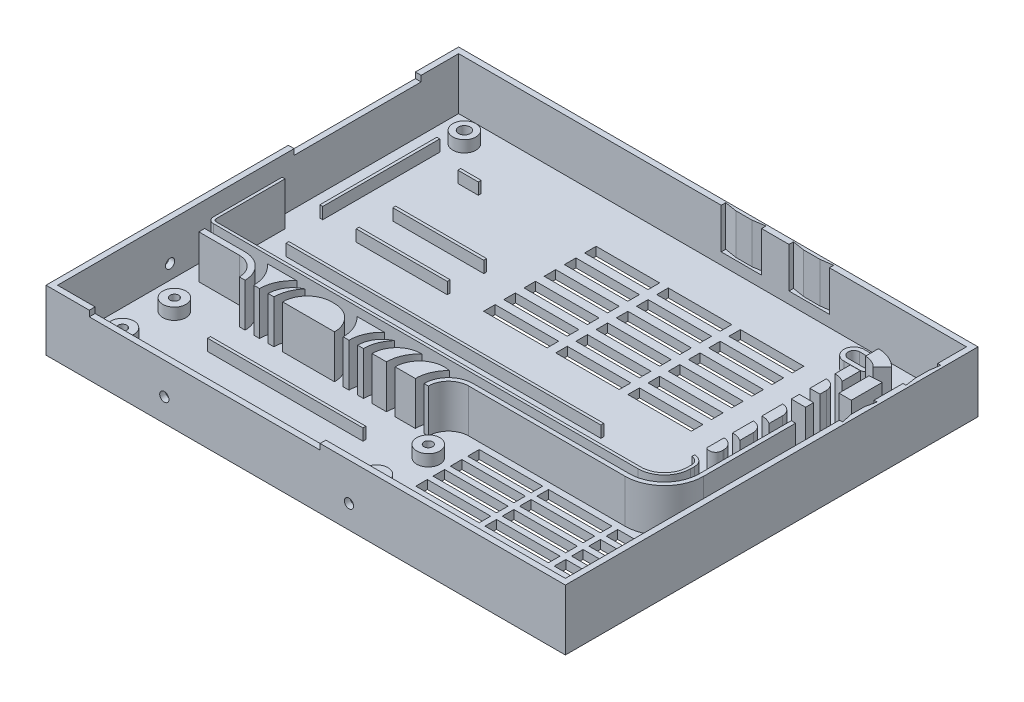
SolidWorks part; units mm, degrees
ref_plane "Front Plane" through (0, 0, 0) normal (0, 0, 1) x (1, 0, 0)
ref_plane "Top Plane" through (0, 0, 0) normal (0, 1, 0) x (1, 0, 0)
ref_plane "Right Plane" through (0, 0, 0) normal (1, 0, 0) x (0, 0, -1)
sketch "Sketch1" plane through (0, 0, 0) normal (0, 1, 0) x (1, 0, 0)
  line L0 (-67.5, 0) -> (67.5, 0) construction
  line L1 (0, 38) -> (0, -38) construction
  line L3 (-67.5, 38) -> (67.5, 38) construction
  line L4 (-67.5, 38) -> (-67.5, -38) construction
  line L5 (-67.5, -38) -> (67.5, -38) construction
  line L6 (67.5, 38) -> (67.5, -38) construction
  line L7 (-67.5, 38) -> (67.5, -38) construction
  line L8 (-67.5, -38) -> (67.5, 38) construction
  line L9 (-71, -71.5) -> (24, -71.5) construction
  line L10 (-23.5, -59) -> (-23.5, -84) construction
  line L11 (-38, -59) -> (-38, -71.5) construction
  line L12 (-17, -59) -> (-17, -71.5) construction
  line L13 (11, -59) -> (11, -71.5) construction
  line L14 (-79.5, 48) -> (-79.5, -95) construction
  line L16 (24, -59) -> (24, -84) construction
  line L17 (-79.5, -95) -> (100.5, -95) construction
  line L18 (100.5, -95) -> (100.5, 48) construction
  line L19 (-71, -59) -> (-71, -84) construction
  line L20 (-71, -84) -> (24, -84) construction
  line L21 (100.5, 48) -> (-79.5, 48) construction
  line L22 (-71, -59) -> (24, -59) construction
  line L23 (0, 38) -> (0, 42) construction
  line L24 (-71.5, 42) -> (71.5, 42) construction
  line L25 (-71.5, 42) -> (-71.5, -42) construction
  line L26 (-71.5, -42) -> (71.5, -42) construction
  line L27 (71.5, 42) -> (71.5, -42) construction
  line L28 (-67.5, 0) -> (-71.5, 0) construction
  line L29 (-43, -59) -> (-43, -71.5) construction
  line L30 (-48, -59) -> (-48, -71.5) construction
  line L31 (-12, -59) -> (-12, -71.5) construction
  line L32 (-7, -59) -> (-7, -71.5) construction
  line L33 (1, -59) -> (1, -71.5) construction
  line L34 (67.5, 38) -> (72.7, 38) construction
  line L35 (67.5, 40) -> (72.7, 40)
  line L36 (67.5, 36) -> (72.7, 36)
  line L37 (67.5, -38) -> (72.6846, -38.4) construction
  line L40 (67.6538, -36.0059) -> (72.8384, -36.4059)
  line L41 (67.3462, -39.9941) -> (72.5307, -40.3941)
  line L42 (-67.5, -38) -> (-67.5, -38.4) construction
  line L43 (-65.5, -38) -> (-65.5, -38.4)
  line L44 (-69.5, -38) -> (-69.5, -38.4)
  circle A0 centre (-67.5, 38) radius 2
  circle A4 centre (-67.5, -62.5) radius 1.5
  circle A8 centre (20.5, -62.5) radius 1.5
  circle A9 centre (20.5, -80.5) radius 1.5
  circle A10 centre (-67.5, -80.5) radius 1.5
  arc A11 (67.5, 40) -> (67.5, 36) centre (67.5, 38) ccw
  arc A12 (72.7, 36) -> (72.7, 40) centre (72.7, 38) ccw
  arc A15 (67.6538, -36.0059) -> (67.3462, -39.9941) centre (67.5, -38) ccw
  arc A16 (72.5307, -40.3941) -> (72.8384, -36.4059) centre (72.6846, -38.4) ccw
  arc A17 (-65.5, -38) -> (-69.5, -38) centre (-67.5, -38) ccw
  arc A18 (-69.5, -38.4) -> (-65.5, -38.4) centre (-67.5, -38.4) ccw
  point P5 (0, 0)
  point P11 (70.1, 38)
  point P13 (-67.5, -38.2)
  point P14 (-23.5, -70)
  point P27 (0, 0)
  point P62 (70.0923, -38.2)
  dimension "D3" = 4
  dimension "D6" = 84
  dimension "D1" = 76
  dimension "D2" = 135
  dimension "D4" = 18
  dimension "D5" = 88
  dimension "D7" = 143
  dimension "D8" = 25
  dimension "D9" = 95
  dimension "D10" = 17
  dimension "D11" = 28
  dimension "D12" = 33
  dimension "D13" = 54
  dimension "D14" = 82
  dimension "D15" = 14.5
  dimension "D16" = 10
  dimension "D17" = 12
  dimension "D18" = 33
  dimension "D19" = 23
  dimension "D20" = 59
  dimension "D21" = 64
  dimension "D22" = 72
  dimension "D23" = 5.2
  dimension "D24" = 4
  dimension "D25" = 4
  dimension "D26" = 5.2
  dimension "D27" = 4
  dimension "D28" = 0.4
  dimension "D29" = 0.4
sketch "CablePath" plane through (0, 0, 0) normal (0, 1, 0) x (1, 0, 0)
  line L0 (-12, -59) -> (-12, -56) construction
  line L5 (101, -94.5) -> (101, 47)
  line L6 (101, 47) -> (-79, 47)
  line L8 (-43, -56) -> (-43, -70.139) construction
  line L9 (-75.5, -42.5222) -> (-75.5, -18.6789) construction
  line L12 (71.5, -29) -> (80.8048, -29) construction
  line L16 (-71.5, -42) -> (71.5, -42) construction
  line L18 (71.5, -18.84) -> (80.8048, -18.84) construction
  line L21 (80.8048, -51.7714) -> (80.8048, 34.0145) construction
  line L22 (30.5, -56) -> (-60.9203, -56) construction
  line L23 (-10.5, -56) -> (-8.5, -56)
  line L24 (71.5, 40.5) -> (71.5, -42) construction
  line L25 (1, -59) -> (1, -56) construction
  line L26 (85.8048, -3.52) -> (85.8048, -35.359) construction
  line L27 (-79, 47) -> (-79, -94.5)
  line L28 (11, -59) -> (11, -56) construction
  line L29 (-79, -94.5) -> (101, -94.5)
  line L30 (-38, -70.139) -> (-38, -56) construction
  line L31 (-43, -59) -> (-43, -71.5) construction
  line L32 (-38, -59) -> (-38, -71.5) construction
  line L33 (71.5, 1.48) -> (80.8048, 1.48) construction
  line L34 (-58, -44.5) -> (-72.0222, -44.5)
  line L35 (75.1637, -46) -> (-33, -46) construction
  line L36 (84.3048, -3.52) -> (84.3048, -8.2028)
  line L37 (-71, -59) -> (24, -59) construction
  line L38 (75.1637, -44.5) -> (-33, -44.5)
  line L39 (71.5, -8.68) -> (80.8048, -8.68) construction
  line L40 (87.3048, -3.52) -> (87.3048, -35.359)
  line L41 (21, -47.5) -> (75.1637, -47.5)
  line L42 (84.3048, -13.68) -> (84.3048, -18.3628)
  line L43 (84.3048, -23.84) -> (84.3048, -24.2165)
  line L44 (84.3048, -3.52) -> (84.3048, -35.359) construction
  line L45 (84.3048, -34) -> (84.3048, -35.359)
  line L46 (-27.8976, -47.4999) -> (-26.899, -47.4999)
  line L47 (75.1637, -47.5) -> (-33, -47.5) construction
  line L48 (2.5, -56) -> (9.5, -56)
  line L49 (-41.5, -56) -> (-39.5, -56)
  line L50 (-36.5, -56) -> (-18.5, -56)
  line L51 (-17, -59) -> (-17, -71.5) construction
  line L52 (21, -49) -> (75.1637, -49)
  line L53 (88.8048, -3.52) -> (88.8048, -35.359)
  line L54 (83.3048, -34) -> (83.3048, -35.359)
  line L55 (75.1637, -43.5) -> (-33, -43.5)
  line L56 (12.5, -56) -> (14, -56)
  line L57 (-58, -46) -> (-72.0222, -46) construction
  line L58 (80.8048, 2.98) -> (80.8048, 5.7849)
  line L59 (80.8048, -0.02) -> (80.8048, -7.18)
  line L60 (80.8048, -10.18) -> (80.8048, -17.34)
  line L61 (80.8048, -20.34) -> (80.8048, -26.2952)
  line L62 (80.8048, -30.5) -> (80.8048, -31.5)
  line L63 (-74, -42.5222) -> (-74, -18.6789)
  line L64 (80.8048, 5.7849) -> (85.7673, 5.7849)
  line L65 (85.7673, 5.7849) -> (85.7673, 2.98)
  line L66 (85.7673, 2.98) -> (80.8048, 2.98)
  line L67 (87.3048, -3.52) -> (88.8048, -3.52)
  line L68 (-7, -59) -> (-7, -56) construction
  line L69 (-17, -59) -> (-17, -56) construction
  line L70 (-48, -59) -> (-48, -56) construction
  line L71 (-58, -43.5) -> (-72.0222, -43.5)
  line L72 (-73, -42.5222) -> (-73, -18.6789)
  line L73 (11, -59) -> (11, -71.5) construction
  line L74 (-58, -47.5) -> (-72.0222, -47.5)
  line L75 (-58, -49.5) -> (-72.0222, -49.5)
  line L76 (-51.5, -56) -> (-49.5, -56)
  line L77 (-72.0222, -47.5) -> (-72.0222, -49.5)
  line L78 (-58, -43.5) -> (-33, -43.5)
  line L79 (-74, -18.6789) -> (-73, -18.6789)
  line L80 (-46.5, -56) -> (-44.5, -56)
  line L81 (-19.2537, -47.5) -> (-9.746, -47.5)
  line L82 (-40.38, -47.1804) -> (-50.62, -47.1804)
  line L83 (-58, -44.5) -> (-33, -44.5)
  line L84 (-15.5, -56) -> (-13.5, -56)
  line L85 (3, -47.5) -> (3.254, -47.5)
  line L86 (-5.5, -56) -> (-0.5, -56)
  line L87 (-71.5, 42) -> (-71.5, -42) construction
  line L88 (67.5, 16.6233) -> (80.8048, 16.6233) construction
  line L89 (67.5, 27.1917) -> (80.8048, 27.1917) construction
  line L90 (67.5, 6.7426) -> (83.9849, 6.7426) construction
  line L91 (85.8048, -3.52) -> (85.8048, 11.6233) construction
  line L92 (85.8048, 11.6233) -> (85.8048, 22.1917) construction
  line L93 (80.8048, 33.1917) -> (80.8048, 28.6917)
  line L94 (85.4191, 26.7697) -> (88.5829, 29.9699)
  line L95 (87.3048, 13.0166) -> (87.3048, 23.4421)
  line L96 (87.3048, 23.4421) -> (91.5804, 23.7236)
  line L97 (84.3065, 23.4421) -> (84.3055, 17.1)
  line L98 (84.3044, 9.4184) -> (80.8048, 9.4184)
  line L99 (80.8048, 9.4184) -> (80.8048, 15.1233)
  line L100 (84.3048, 11.6233) -> (84.3044, 9.4184)
  line L101 (80.8048, 18.1233) -> (80.8048, 23.4421)
  line L102 (91.5804, 23.7236) -> (91.5804, 13.0166)
  line L103 (91.5804, 13.0166) -> (87.3048, 13.0166)
  line L104 (84.3065, 23.4421) -> (80.8048, 23.4421)
  arc A0 (14, -56) -> (21, -49) centre (21, -56) cw
  circle A1 centre (-67.5, -62.5) radius 1.5 construction
  arc A2 (9.5, -56) -> (21, -44.5) centre (21, -56) cw construction
  arc A3 (75.1637, -49) -> (88.8048, -35.359) centre (75.1637, -35.359) ccw
  arc A4 (85.4191, 26.7697) -> (80.8048, 28.6917) centre (80.8048, 22.1917) ccw
  arc A5 (88.5829, 29.9699) -> (80.8048, 33.1917) centre (80.8048, 22.1917) ccw
  arc A7 (84.3055, 17.1) -> (80.8048, 18.1233) centre (80.8048, 11.6233) ccw
  circle A8 centre (-67.5, -80.5) radius 1.5 construction
  circle A9 centre (-67.5, -62.5) radius 1.5
  circle A10 centre (20.5, -62.5) radius 1.5 construction
  circle A11 centre (-67.5, -80.5) radius 1.5
  arc A12 (80.8048, -26.2952) -> (84.3048, -24.2165) centre (82.1448, -24.5655) ccw
  arc A13 (85.8048, 22.1917) -> (80.8048, 27.1917) centre (80.8048, 22.1917) ccw construction
  arc A14 (85.8048, 11.6233) -> (80.8048, 16.6233) centre (80.8048, 11.6233) ccw construction
  arc A15 (84.3048, 11.6233) -> (80.8048, 15.1233) centre (80.8048, 11.6233) ccw
  arc A16 (80.8048, 1.48) -> (85.8048, -3.52) centre (80.8048, -3.52) cw construction
  arc A17 (80.8048, -8.68) -> (85.8048, -13.68) centre (80.8048, -13.68) cw construction
  arc A18 (80.8048, -18.84) -> (85.8048, -23.84) centre (80.8048, -23.84) cw construction
  arc A19 (80.8048, -29) -> (85.8048, -34) centre (80.8048, -34) cw construction
  arc A20 (75.1637, -46) -> (85.8048, -35.359) centre (75.1637, -35.359) ccw construction
  arc A21 (-43, -56) -> (-33, -46) centre (-33, -56) cw construction
  arc A22 (-38, -56) -> (-27.8796, -46) centre (-27.9993, -56) cw construction
  arc A23 (1, -56) -> (11, -46) centre (11, -56) cw construction
  arc A24 (11, -56) -> (21, -46) centre (21, -56) cw construction
  circle A25 centre (20.5, -62.5) radius 1.5
  circle A26 centre (20.5, -80.5) radius 1.5 construction
  circle A27 centre (20.5, -80.5) radius 1.5
  arc A28 (80.8048, -0.02) -> (84.3048, -3.52) centre (80.8048, -3.52) cw
  arc A29 (75.1637, -44.5) -> (84.3048, -35.359) centre (75.1637, -35.359) ccw
  arc A30 (-44.5, -56) -> (-40.38, -47.1804) centre (-33, -56) cw
  arc A31 (80.8048, -10.18) -> (84.3048, -13.68) centre (80.8048, -13.68) cw
  arc A32 (80.8048, -20.34) -> (84.3048, -23.84) centre (80.8048, -23.84) cw
  arc A33 (80.8048, -30.5) -> (84.3048, -34) centre (80.8048, -34) cw
  arc A34 (12.5, -56) -> (21, -47.5) centre (21, -56) cw
  arc A35 (2.5, -56) -> (13, -47.7386) centre (11, -56) cw
  arc A36 (-36.5, -56) -> (-27.8976, -47.4999) centre (-27.9993, -56) cw
  arc A37 (80.8048, 2.98) -> (87.3048, -3.52) centre (80.8048, -3.52) cw construction
  arc A38 (75.1637, -47.5) -> (87.3048, -35.359) centre (75.1637, -35.359) ccw
  arc A39 (-41.5, -56) -> (-36.5004, -48.2542) centre (-33, -56) cw
  arc A40 (80.8048, -7.18) -> (84.3048, -8.2028) centre (80.8048, -13.68) cw
  arc A41 (80.8048, -17.34) -> (84.3048, -18.3628) centre (80.8048, -23.84) cw
  arc A43 (9.5, -56) -> (13, -47.7386) centre (21, -56) cw
  arc A44 (-0.5, -56) -> (3.254, -47.5) centre (11, -56) cw
  arc A45 (-39.5, -56) -> (-36.5004, -48.2542) centre (-27.9993, -56) cw
  arc A46 (-39.5, -56) -> (-27.8617, -44.5001) centre (-27.9993, -56) cw construction
  arc A47 (87.3048, 11.6233) -> (80.8048, 18.1233) centre (80.8048, 11.6233) ccw construction
  arc A48 (80.8048, -7.18) -> (87.3048, -13.68) centre (80.8048, -13.68) cw construction
  arc A49 (80.8048, -17.34) -> (87.3048, -23.84) centre (80.8048, -23.84) cw construction
  arc A50 (80.8048, 4.48) -> (88.8048, -3.52) centre (80.8048, -3.52) cw construction
  arc A51 (-0.5, -56) -> (11, -44.5) centre (11, -56) cw construction
  arc A52 (80.8048, -31.5) -> (83.3048, -34) centre (80.8048, -34) cw
  arc A53 (75.1637, -43.5) -> (83.3048, -35.359) centre (75.1637, -35.359) ccw
  arc A54 (-48, -56) -> (-58, -46) centre (-58, -56) ccw construction
  arc A55 (-17, -56) -> (-26.881, -46) centre (-27.0007, -56) ccw construction
  arc A56 (-41.5, -56) -> (-33, -47.5) centre (-33, -56) cw construction
  arc A57 (-45.5, -56) -> (-33, -43.5) centre (-33, -56) cw construction
  arc A58 (-72.0222, -46) -> (-75.5, -42.5222) centre (-72.0222, -42.5222) cw construction
  arc A59 (-46.5, -56) -> (-50.62, -47.1804) centre (-58, -56) ccw
  arc A60 (-72.0222, -44.5) -> (-74, -42.5222) centre (-72.0222, -42.5222) cw
  arc A61 (-15.5, -56) -> (-19.2537, -47.5) centre (-27.0007, -56) ccw
  arc A62 (-72.0222, -43.5) -> (-73, -42.5222) centre (-72.0222, -42.5222) cw
  arc A63 (-49.5, -56) -> (-58, -47.5) centre (-58, -56) ccw
  arc A64 (-51.5, -56) -> (-58, -49.5) centre (-58, -56) ccw
  arc A65 (-45.5, -56) -> (-58, -43.5) centre (-58, -56) ccw construction
  arc A66 (-18.5, -56) -> (-26.899, -47.4999) centre (-27.0007, -56) ccw
  arc A67 (-12, -56) -> (-2, -46) centre (-2, -56) cw construction
  arc A68 (-15.5, -56) -> (-26.8631, -44.5001) centre (-27.0007, -56) ccw construction
  arc A69 (-46.5, -56) -> (-58, -44.5) centre (-58, -56) ccw construction
  arc A70 (-44.5, -56) -> (-33, -44.5) centre (-33, -56) cw construction
  arc A71 (2.5, -56) -> (11, -47.5) centre (11, -56) cw construction
  arc A72 (-7, -56) -> (3, -46) centre (3, -56) cw construction
  arc A73 (-10.5, -56) -> (-5.5, -48.254) centre (-2, -56) cw
  arc A74 (-5.5, -56) -> (3, -47.5) centre (3, -56) cw
  arc A75 (-13.5, -56) -> (-9.746, -47.5) centre (-2, -56) cw
  arc A76 (-8.5, -56) -> (-5.5, -48.254) centre (3, -56) cw
  arc A77 (87.3048, 22.1917) -> (80.8048, 28.6917) centre (80.8048, 22.1917) ccw construction
  arc A78 (-13.5, -56) -> (-2, -44.5) centre (-2, -56) cw construction
  arc A79 (-10.5, -56) -> (-2, -47.5) centre (-2, -56) cw construction
  arc A80 (91.8048, 22.1917) -> (80.8048, 33.1917) centre (80.8048, 22.1917) ccw construction
  arc A81 (-8.5, -56) -> (3, -44.5) centre (3, -56) cw construction
  point P0 (67.5, -38)
  point P7 (67.5, 38)
  point P10 (-67.5, -80.5)
  point P117 (77.6351, -51.5)
  point P118 (-14.035, -51.5)
  point P127 (77.6351, -54.5)
  point P128 (-14.035, -54.5)
  point P132 (79.6209, -33.364)
  point P134 (85.4849, -33.364)
  point P137 (3.3488, -47.5)
  point P138 (3.3488, -61)
  point P139 (-10.1512, -61)
  point P146 (3.3488, -50.5)
  point P147 (3.3488, -61)
  point P148 (-7.1512, -61)
  point P154 (80.8048, 22.2244)
  point P242 (3.4721, -55.4721)
  point P243 (-8, -55.4721)
  point P244 (3.4721, -44)
  point P253 (87.3048, 22.2244)
  point P256 (80.8048, 22.2244)
  point P257 (91.8048, 22.2244)
  dimension "D5" = 10.16
  dimension "D8" = 3
  dimension "D23" = 1.5
  dimension "D24" = 5
  dimension "D25" = 5
  dimension "D1" = 1.5
  dimension "D3" = 4
  dimension "D4" = 13
  dimension "D6" = 10.16
  dimension "D7" = 10.16
  dimension "D9" = 3.5
  dimension "D10" = 1.5
  dimension "D11" = 1.5
  dimension "D12" = 1
  dimension "D13" = 1.5
  dimension "D14" = 1
  dimension "D15" = 1.5
  dimension "D16" = 2
  dimension "D17" = 1.5
  dimension "D18" = 1.5
  dimension "D28" = 180
  dimension "D19" = 1.5
  dimension "D20" = 1.5
  dimension "D21" = 1.5
  dimension "D22" = 1.5
  dimension "D26" = 1.5
  dimension "D27" = 6
  dimension "D30" = 1.5
  dimension "D31" = 1.5
sketch "Bottom" plane through (0, 0, 0) normal (0, 1, 0) x (1, 0, 0)
  line L0 (-79.5, 48) -> (-79.5, -95) construction
  line L1 (-79.5, 48) -> (-79.5, -95)
  line L2 (-79.5, -95) -> (100.5, -95) construction
  line L3 (-79.5, -95) -> (100.5, -95)
  line L4 (67.6538, -36.0059) -> (72.8384, -36.4059) construction
  line L5 (67.3462, -39.9941) -> (72.5307, -40.3941) construction
  line L6 (100.5, -95) -> (100.5, 48) construction
  line L7 (100.5, -95) -> (100.5, 48)
  line L8 (100.5, 48) -> (-79.5, 48) construction
  line L9 (100.5, 48) -> (-79.5, 48)
  line L10 (67.6538, -36.0059) -> (72.8384, -36.4059)
  line L11 (67.3462, -39.9941) -> (72.5307, -40.3941)
  line L12 (67.5, 36) -> (72.7, 36) construction
  line L13 (67.5, 40) -> (72.7, 40) construction
  line L14 (67.5, 36) -> (72.7, 36)
  line L15 (67.5, 40) -> (72.7, 40)
  line L16 (-65.5, -38) -> (-65.5, -38.4) construction
  line L17 (-69.5, -38) -> (-69.5, -38.4) construction
  line L18 (-65.5, -38) -> (-65.5, -38.4)
  line L19 (-69.5, -38) -> (-69.5, -38.4)
  arc A0 (72.5307, -40.3941) -> (72.8384, -36.4059) centre (72.6846, -38.4) ccw construction
  arc A1 (67.6538, -36.0059) -> (67.3462, -39.9941) centre (67.5, -38) ccw construction
  arc A2 (72.5307, -40.3941) -> (72.8384, -36.4059) centre (72.6846, -38.4) ccw
  arc A3 (67.6538, -36.0059) -> (67.3462, -39.9941) centre (67.5, -38) ccw
  arc A4 (72.7, 36) -> (72.7, 40) centre (72.7, 38) ccw construction
  arc A5 (67.5, 40) -> (67.5, 36) centre (67.5, 38) ccw construction
  arc A6 (72.7, 36) -> (72.7, 40) centre (72.7, 38) ccw
  arc A7 (67.5, 40) -> (67.5, 36) centre (67.5, 38) ccw
  circle A8 centre (-67.5, 38) radius 2 construction
  circle A9 centre (-67.5, 38) radius 2
  arc A10 (-69.5, -38.4) -> (-65.5, -38.4) centre (-67.5, -38.4) ccw construction
  arc A11 (-65.5, -38) -> (-69.5, -38) centre (-67.5, -38) ccw construction
  arc A12 (-69.5, -38.4) -> (-65.5, -38.4) centre (-67.5, -38.4) ccw
  arc A13 (-65.5, -38) -> (-69.5, -38) centre (-67.5, -38) ccw
  dimension "D1" = 143
  dimension "D2" = 180
extrude "Boss-Bottom" add sketch "Bottom" along normal blind 3
sketch "PCBmount" plane through (0, 3, 0) normal (0, 1, 0) x (1, 0, 0)
  line L0 (-49.5761, -67.9069) -> (-49.5761, -68.9069)
  line L1 (-49.5761, -67.9069) -> (4.2504, -67.9069)
  line L2 (-49.5761, -68.9069) -> (4.2504, -68.9069)
  line L3 (4.2504, -67.9069) -> (4.2504, -68.9069)
  line L5 (-64.5007, -25.8146) -> (44.6202, -25.8146)
  line L6 (-64.5007, -25.8146) -> (-64.5007, -26.8146)
  line L7 (44.6202, -25.8146) -> (44.6202, -26.8146)
  line L8 (-64.5007, -26.8146) -> (44.6202, -26.8146)
  line L9 (-56.6714, -10.3272) -> (-25.1095, -10.3272)
  line L10 (-56.6714, -10.3272) -> (-56.6714, -9.3272)
  line L11 (-25.1095, -10.3272) -> (-25.1095, -9.3272)
  line L12 (-56.6714, -9.3272) -> (-25.1095, -9.3272)
  line L13 (-56.6714, 2.3448) -> (-25.1095, 2.3448)
  line L14 (-56.6714, 2.3448) -> (-56.6714, 3.3448)
  line L15 (-25.1095, 2.3448) -> (-25.1095, 3.3448)
  line L16 (-56.6714, 3.3448) -> (-25.1095, 3.3448)
  line L17 (-70.1846, -9.4098) -> (-69.1846, -9.4098)
  line L18 (-70.1846, -9.4098) -> (-70.1846, 31.1536)
  line L19 (-69.1846, -9.4098) -> (-69.1846, 31.1536)
  line L20 (-70.1846, 31.1536) -> (-69.1846, 31.1536)
  line L21 (-56.6714, 24.8918) -> (-49.5761, 24.8918)
  line L22 (-56.6714, 24.8918) -> (-56.6714, 25.8918)
  line L23 (-49.5761, 24.8918) -> (-49.5761, 25.8918)
  line L24 (-56.6714, 25.8918) -> (-49.5761, 25.8918)
  line L30 (67.5, 36) -> (72.7, 36) construction
  line L31 (67.5, 40) -> (72.7, 40) construction
  line L32 (-67.5, 0) -> (67.5, 0) construction
  line L33 (-67.5, 0) -> (67.5, 0) construction
  line L34 (67.5, 36) -> (72.7, 36)
  line L35 (67.5, 40) -> (72.7, 40)
  line L38 (-65.5, -38) -> (-65.5, -38.4) construction
  line L39 (-69.5, -38) -> (-69.5, -38.4) construction
  line L40 (-65.5, -38) -> (-65.5, -38.4)
  line L41 (-69.5, -38) -> (-69.5, -38.4)
  line L42 (-64, -38) -> (-64, -38.4)
  line L43 (-71, -38) -> (-71, -38.4)
  line L44 (67.5, 34.5) -> (72.7, 34.5)
  line L45 (67.5, 41.5) -> (72.7, 41.5)
  line L46 (67.6538, -36.0059) -> (72.8384, -36.4059) construction
  line L47 (67.3462, -39.9941) -> (72.5307, -40.3941) construction
  line L48 (67.6538, -36.0059) -> (72.8384, -36.4059)
  line L49 (67.3462, -39.9941) -> (72.5307, -40.3941)
  line L50 (67.7692, -34.5104) -> (72.9538, -34.9104)
  line L51 (67.2308, -41.4896) -> (72.4154, -41.8896)
  circle A4 centre (-67.5, -62.5) radius 1.5 construction
  circle A6 centre (-67.5, 38) radius 2 construction
  circle A8 centre (20.5, -80.5) radius 1.5 construction
  circle A9 centre (20.5, -62.5) radius 1.5 construction
  arc A10 (72.7, 36) -> (72.7, 40) centre (72.7, 38) ccw construction
  circle A11 centre (-67.5, -80.5) radius 1.5 construction
  circle A12 centre (-67.5, -62.5) radius 1.5
  arc A13 (-65.5, -38) -> (-69.5, -38) centre (-67.5, -38) ccw construction
  circle A14 centre (-67.5, 38) radius 2
  circle A16 centre (-67.5, 38) radius 4
  arc A17 (67.5, 40) -> (67.5, 36) centre (67.5, 38) ccw construction
  arc A18 (72.7, 36) -> (72.7, 40) centre (72.7, 38) ccw
  arc A19 (-69.5, -38.4) -> (-65.5, -38.4) centre (-67.5, -38.4) ccw construction
  circle A20 centre (-67.5, -62.5) radius 4
  circle A21 centre (-67.5, -80.5) radius 4
  circle A22 centre (20.5, -80.5) radius 4
  circle A23 centre (20.5, -62.5) radius 4
  circle A24 centre (-67.5, -80.5) radius 1.5
  circle A25 centre (20.5, -80.5) radius 1.5
  circle A26 centre (20.5, -62.5) radius 1.5
  arc A27 (67.5, 40) -> (67.5, 36) centre (67.5, 38) ccw
  arc A30 (-65.5, -38) -> (-69.5, -38) centre (-67.5, -38) ccw
  arc A31 (-69.5, -38.4) -> (-65.5, -38.4) centre (-67.5, -38.4) ccw
  arc A32 (-71, -38.4) -> (-64, -38.4) centre (-67.5, -38.4) ccw
  arc A33 (-64, -38) -> (-71, -38) centre (-67.5, -38) ccw
  arc A34 (72.7, 34.5) -> (72.7, 41.5) centre (72.7, 38) ccw
  arc A35 (67.5, 41.5) -> (67.5, 34.5) centre (67.5, 38) ccw
  arc A36 (72.5307, -40.3941) -> (72.8384, -36.4059) centre (72.6846, -38.4) ccw construction
  arc A37 (67.6538, -36.0059) -> (67.3462, -39.9941) centre (67.5, -38) ccw construction
  arc A38 (72.5307, -40.3941) -> (72.8384, -36.4059) centre (72.6846, -38.4) ccw
  arc A39 (67.6538, -36.0059) -> (67.3462, -39.9941) centre (67.5, -38) ccw
  arc A40 (72.4154, -41.8896) -> (72.9538, -34.9104) centre (72.6846, -38.4) ccw
  arc A41 (67.7692, -34.5104) -> (67.2308, -41.4896) centre (67.5, -38) ccw
  dimension "D1" = 8
  dimension "D2" = 8
  dimension "D3" = 1
  dimension "D5" = 1.5
  dimension "D6" = 1.5
  dimension "D4" = 1.5
extrude "Boss-PCBmount" add sketch "PCBmount" along normal blind 4
sketch "Sides" plane through (0, 3, 0) normal (0, 1, 0) x (1, 0, 0)
  line L0 (-79.5, -95) -> (100.5, -95) construction
  line L1 (100.5, -95) -> (100.5, 48) construction
  line L2 (-79.5, 48) -> (-79.5, -95) construction
  line L3 (100.5, 48) -> (-79.5, 48) construction
  line L4 (-79.5, -95) -> (100.5, -95)
  line L5 (100.5, -95) -> (100.5, 48)
  line L6 (-79.5, 48) -> (-79.5, -95)
  line L7 (100.5, 48) -> (-79.5, 48)
  line L8 (-77.5, -93) -> (98.5, -93)
  line L9 (98.5, -93) -> (98.5, 46)
  line L10 (98.5, 46) -> (-77.5, 46)
  line L11 (-77.5, 46) -> (-77.5, -93)
  dimension "D1" = 2
extrude "Boss-Sides" add sketch "Sides" along normal blind 18
sketch "24VHeatBedTabort" plane through (100.5, 0, 0) normal (1, 0, 0) x (0, 0, -1)
  line L0 (36, 21) -> (36, 9)
  line L1 (48, 21) -> (48, 0) construction
  line L2 (36, 9) -> (24, 9)
  line L3 (24, 9) -> (24, 21)
  line L4 (24, 21) -> (36, 21)
  line L5 (14, 21) -> (14, 9)
  line L6 (14, 9) -> (2, 9)
  line L7 (2, 9) -> (2, 21)
  line L8 (2, 21) -> (14, 21)
  line L10 (-95, 21) -> (48, 21) construction
  dimension "D3" = 12
  dimension "D5" = 12
  dimension "D6" = 10
extrude "Boss-CablePath" add sketch "CablePath" along normal blind 18 contours A74 L85 A44 L86 | A76 A73 L23 | A75 L81 A61 L84 | L38 L83 L34 A60 L63 L79 L72 A62 L71 L78 L55 A53 L54 A52 L62 A33 L45 A29 | A66 L46 A36 L50 | A35 A43 L48 | A34 L41 A38 L40 L67 L53 A3 L52 A0 L56 | L75 L77 L74 A63 L76 A64 | A59 L82 A30 L80 | A39 A45 L49 | L43 A12 L61 A32 | L42 A41 L60 A31 | L36 A40 L59 A28 | L65 L66 L58 L64 | L100 L98 L99 A15 | L97 A7 L101 L104 | L93 A4 L94 A5 | L102 L103 L95 L96
sketch "Fan" plane through (0, 3, 0) normal (0, 1, 0) x (1, 0, 0)
  line L1 (55.5, -50) -> (95.5, -50) construction
  line L2 (55.5, -50) -> (55.5, -90) construction
  line L3 (55.5, -90) -> (95.5, -90) construction
  line L4 (95.5, -50) -> (95.5, -90) construction
  line L5 (55.5, -50) -> (95.5, -90) construction
  line L6 (55.5, -90) -> (95.5, -50) construction
  line L8 (98.5, -93) -> (98.5, 46) construction
  line L9 (-77.5, -93) -> (98.5, -93) construction
  circle A0 centre (75.5, -70) radius 19
  circle A1 centre (75.5, -70) radius 10
  arc A2 (75.5, -70) -> (75.5, -51) centre (80.3261, -60.5) cw
  arc A3 (75.5, -70) -> (91.9545, -60.5) centre (86.1403, -69.4295) cw
  arc A4 (75.5, -70) -> (91.9545, -79.5) centre (81.3142, -78.9295) cw
  arc A5 (75.5, -70) -> (75.5, -89) centre (70.6739, -79.5) cw
  arc A6 (75.5, -70) -> (59.0455, -79.5) centre (64.8597, -70.5705) cw
  arc A7 (75.5, -70) -> (59.0455, -60.5) centre (69.6858, -61.0705) cw
  point P0 (75.5, -70)
  point P27 (75.5, -70)
  dimension "D5" = 38
  dimension "D6" = 20
  dimension "D1" = 40
  dimension "D2" = 40
  dimension "D3" = 3
  dimension "D4" = 3
  dimension "D7" = 6
sketch "FanHoles" plane through (0, 0, 0) normal (0, -1, 0) x (1, 0, 0)
  line L0 (55.5, 90) -> (95.5, 50) construction
  line L1 (55.5, 90) -> (95.5, 50) construction
  line L2 (55.5, 50) -> (95.5, 90) construction
  line L3 (55.5, 50) -> (95.5, 90) construction
  line L4 (55.5, 50) -> (95.5, 50) construction
  line L5 (55.5, 50) -> (95.5, 50) construction
  line L6 (55.5, 90) -> (95.5, 90) construction
  line L7 (55.5, 90) -> (95.5, 90) construction
  line L8 (55.5, 50) -> (55.5, 90) construction
  line L9 (55.5, 50) -> (55.5, 90) construction
  line L10 (95.5, 50) -> (95.5, 90) construction
  line L11 (95.5, 50) -> (95.5, 90) construction
  line L12 (75.5, 50) -> (75.5, 90) construction
  line L13 (55.5, 70) -> (95.5, 70) construction
  circle A1 centre (59.5, 54) radius 1.5
  circle A2 centre (59.5, 86) radius 1.5
  circle A6 centre (91.5, 86) radius 1.5
  circle A7 centre (91.5, 54) radius 1.5
  dimension "D1" = 32
  dimension "D2" = 32
sketch "ExtruderCables" plane through (0, 0, 95) normal (0, 0, 1) x (1, 0, 0)
  line L0 (-79.5, 21) -> (-79.5, 0) construction
  line L1 (-64.5, 21) -> (15.5, 21)
  line L2 (-64.5, 21) -> (-64.5, 19)
  line L3 (-64.5, 19) -> (15.5, 19)
  line L4 (15.5, 21) -> (15.5, 19)
  line L5 (-64.5, 21) -> (15.5, 19) construction
  line L6 (-64.5, 19) -> (15.5, 21) construction
  line L7 (-79.5, 21) -> (100.5, 21) construction
  point P0 (-24.5, 20)
  dimension "D1" = 15
  dimension "D2" = 80
extrude "Cut-ExtruderCables" cut sketch "ExtruderCables" against normal up to surface (2 mm away) up to face at (10.5, 12, 93)
sketch "LCD" plane through (-79.5, 0, 0) normal (-1, 0, 0) x (0, 0, 1)
  line L0 (-33, 21) -> (-33, 19)
  line L1 (-33, 21) -> (11, 21)
  line L2 (-33, 19) -> (11, 19)
  line L3 (11, 21) -> (11, 19)
  line L4 (-48, 21) -> (95, 21) construction
  line L5 (-48, 21) -> (-48, 0) construction
  dimension "D1" = 15
  dimension "D2" = 59
extrude "Cut-LCD" cut sketch "LCD" against normal up to surface (2 mm away) up to face at (-77.5, 12, 23.5)
sketch "Sketch2" plane through (0, 0, 0) normal (0, -1, 0) x (1, 0, 0)
  line L0 (-79.5, -48) -> (-79.5, 95) construction
  line L3 (-79.5, 95) -> (100.5, 95) construction
  line L4 (35.5, 123) -> (35.5, 95)
  line L5 (-98.5, -48) -> (-98.5, 143.5262) construction
  line L6 (-104.4968, 114) -> (115.2818, 114) construction
  line L7 (35.5, 123) -> (-48.5, 123)
  line L8 (-107.5, 64) -> (-107.5, 6)
  line L9 (35.5, 95) -> (-48.5, 95)
  line L10 (-79.5, 64) -> (-79.5, 6)
  line L11 (-48.5, 95) -> (-48.5, 123)
  line L13 (-79.5, 6) -> (-107.5, 6)
  line L14 (-107.5, 64) -> (-79.5, 64)
  line L15 (-79.5, 95) -> (-79.5, 123) construction
  line L16 (-79.5, 95) -> (-116.8086, 95) construction
  line L17 (-107.5, 95) -> (-107.5, 123) construction
  line L18 (-107.5, 123) -> (-79.5, 123) construction
  circle A0 centre (-98.5, 16) radius 2.5
  circle A1 centre (-98.5, 54) radius 2.5
  circle A2 centre (-38.5, 114) radius 2.5
  circle A3 centre (25.5, 114) radius 2.5
  dimension "D2" = 28
  dimension "D4" = 60
  dimension "D5" = 60
  dimension "D12" = 10
  dimension "D3" = 38
  dimension "D6" = 64
  dimension "D7" = 28
  dimension "D8" = 9
  dimension "D9" = 9
  dimension "D10" = 10
  dimension "D11" = 10
  dimension "D13" = 10
sketch "USB" plane through (0, 21, 0) normal (0, 1, 0) x (1, 0, 0)
  line L0 (37, 46) -> (51, 46)
  line L1 (98.5, 46) -> (-77.5, 46) construction
  line L2 (51, 46) -> (51, 47.4707)
  line L3 (4.6819, 46.8766) -> (57.5762, 46.8766) construction
  line L4 (13.5, 47.5631) -> (17.6913, 46.8766)
  line L5 (37, 47.5631) -> (41.1913, 46.8766)
  line L6 (37, 47.5631) -> (37, 46)
  line L7 (100.5, -95) -> (100.5, 48) construction
  line L8 (27.5, 46) -> (13.5, 46)
  line L9 (13.5, 46) -> (13.5, 47.5631)
  line L10 (27.5, 47.5504) -> (23.3067, 46.8766)
  line L11 (51, 47.4707) -> (46.7946, 46.8766)
  line L12 (17.6913, 46.8766) -> (23.3067, 46.8766)
  line L13 (27.5, 47.5504) -> (27.5, 46)
  line L14 (41.1913, 46.8766) -> (46.7946, 46.8766)
  dimension "D1" = 14
  dimension "D2" = 49.5
  dimension "D3" = 73
extrude "Cut-USB" cut sketch "USB" against normal blind 14
sketch "24VHeatBed" plane through (0, 21, 0) normal (0, 1, 0) x (1, 0, 0)
  line L0 (98.5, 2) -> (98.5, 8)
  line L1 (98.5, -93) -> (98.5, 46) construction
  line L2 (99.6005, 14) -> (98.5, 14)
  line L3 (98.7901, 10.3221) -> (99.6005, 14)
  line L4 (98.7901, 8) -> (98.7901, 5.6779)
  line L5 (98.7901, 5.6779) -> (99.6005, 2)
  line L6 (99.6005, 2) -> (98.5, 2)
  line L7 (98.5, 8) -> (100.5, 8) construction
  line L8 (100.5, 2) -> (100.5, 14) construction
  line L9 (98.7901, 8) -> (98.7901, 10.3221)
  line L10 (98.5, 14) -> (98.5, 8)
  line L11 (98.5, 24) -> (98.4993, 30)
  line L12 (99.5701, 36) -> (98.5, 36)
  line L13 (99.0353, 32.3221) -> (99.5701, 36)
  line L14 (99.0353, 30) -> (99.0353, 27.6779)
  line L15 (99.0353, 27.6779) -> (99.5701, 24)
  line L16 (99.5701, 24) -> (98.5, 24)
  line L17 (98.4993, 30) -> (100.5, 30) construction
  line L18 (100.5, 24) -> (100.5, 36) construction
  line L19 (99.0353, 30) -> (99.0353, 32.3221)
  line L20 (98.5, 36) -> (98.4993, 30)
  line L21 (100.5, 48) -> (-79.5, 48) construction
  dimension "D1" = 12
  dimension "D2" = 12
extrude "Cut-Extrude1" cut sketch "24VHeatBed" against normal blind 12
sketch "AirOut" plane through (0, 3, 0) normal (0, 1, 0) x (1, 0, 0)
  line L0 (50.8814, -87.2405) -> (72.8814, -87.2405)
  line L1 (74.8814, -87.2405) -> (96.8814, -87.2405)
  line L2 (74.8814, -87.2405) -> (74.8814, -91.2405)
  line L3 (74.8814, -91.2405) -> (96.8814, -91.2405)
  line L4 (96.8814, -87.2405) -> (96.8814, -91.2405)
  line L5 (74.8814, -87.2405) -> (96.8814, -91.2405) construction
  line L6 (74.8814, -91.2405) -> (96.8814, -87.2405) construction
  line L7 (50.8814, -87.2405) -> (50.8814, -91.2405)
  line L8 (50.8814, -91.2405) -> (72.8814, -91.2405)
  line L9 (72.8814, -87.2405) -> (72.8814, -91.2405)
  line L10 (26.8814, -87.2405) -> (48.8814, -87.2405)
  line L11 (26.8814, -87.2405) -> (26.8814, -91.2405)
  line L12 (26.8814, -91.2405) -> (48.8814, -91.2405)
  line L13 (48.8814, -87.2405) -> (48.8814, -91.2405)
  line L14 (50.8814, -81.2405) -> (72.8814, -81.2405)
  line L15 (50.8814, -81.2405) -> (50.8814, -85.2405)
  line L16 (50.8814, -85.2405) -> (72.8814, -85.2405)
  line L17 (72.8814, -81.2405) -> (72.8814, -85.2405)
  line L18 (26.8814, -81.2405) -> (48.8814, -81.2405)
  line L19 (26.8814, -81.2405) -> (26.8814, -85.2405)
  line L20 (26.8814, -85.2405) -> (48.8814, -85.2405)
  line L21 (48.8814, -81.2405) -> (48.8814, -85.2405)
  line L22 (50.8814, -75.2405) -> (72.8814, -75.2405)
  line L23 (50.8814, -75.2405) -> (50.8814, -79.2405)
  line L24 (50.8814, -79.2405) -> (72.8814, -79.2405)
  line L25 (72.8814, -75.2405) -> (72.8814, -79.2405)
  line L26 (26.8814, -75.2405) -> (48.8814, -75.2405)
  line L27 (26.8814, -75.2405) -> (26.8814, -79.2405)
  line L28 (26.8814, -79.2405) -> (48.8814, -79.2405)
  line L29 (48.8814, -75.2405) -> (48.8814, -79.2405)
  line L30 (50.8814, -69.2405) -> (72.8814, -69.2405)
  line L31 (50.8814, -69.2405) -> (50.8814, -73.2405)
  line L32 (50.8814, -73.2405) -> (72.8814, -73.2405)
  line L33 (72.8814, -69.2405) -> (72.8814, -73.2405)
  line L34 (26.8814, -69.2405) -> (48.8814, -69.2405)
  line L35 (26.8814, -69.2405) -> (26.8814, -73.2405)
  line L36 (26.8814, -73.2405) -> (48.8814, -73.2405)
  line L37 (48.8814, -69.2405) -> (48.8814, -73.2405)
  line L38 (50.8814, -63.2405) -> (72.8814, -63.2405)
  line L39 (50.8814, -63.2405) -> (50.8814, -67.2405)
  line L40 (50.8814, -67.2405) -> (72.8814, -67.2405)
  line L41 (72.8814, -63.2405) -> (72.8814, -67.2405)
  line L42 (26.8814, -63.2405) -> (48.8814, -63.2405)
  line L43 (26.8814, -63.2405) -> (26.8814, -67.2405)
  line L44 (26.8814, -67.2405) -> (48.8814, -67.2405)
  line L45 (48.8814, -63.2405) -> (48.8814, -67.2405)
  line L46 (74.8814, -81.2405) -> (96.8814, -81.2405)
  line L47 (74.8814, -81.2405) -> (74.8814, -85.2405)
  line L48 (74.8814, -85.2405) -> (96.8814, -85.2405)
  line L49 (96.8814, -81.2405) -> (96.8814, -85.2405)
  line L50 (74.8814, -75.2405) -> (96.8814, -75.2405)
  line L51 (74.8814, -75.2405) -> (74.8814, -79.2405)
  line L52 (74.8814, -79.2405) -> (96.8814, -79.2405)
  line L53 (96.8814, -75.2405) -> (96.8814, -79.2405)
  line L54 (74.8814, -69.2405) -> (96.8814, -69.2405)
  line L55 (74.8814, -69.2405) -> (74.8814, -73.2405)
  line L56 (74.8814, -73.2405) -> (96.8814, -73.2405)
  line L57 (96.8814, -69.2405) -> (96.8814, -73.2405)
  line L58 (74.8814, -63.2405) -> (96.8814, -63.2405)
  line L59 (74.8814, -63.2405) -> (74.8814, -67.2405)
  line L60 (74.8814, -67.2405) -> (96.8814, -67.2405)
  line L61 (96.8814, -63.2405) -> (96.8814, -67.2405)
  line L62 (74.8814, -57.2405) -> (96.8814, -57.2405)
  line L63 (74.8814, -57.2405) -> (74.8814, -61.2405)
  line L64 (74.8814, -61.2405) -> (96.8814, -61.2405)
  line L65 (96.8814, -57.2405) -> (96.8814, -61.2405)
  line L66 (50.8814, -57.2405) -> (72.8814, -57.2405)
  line L67 (50.8814, -57.2405) -> (50.8814, -61.2405)
  line L68 (50.8814, -61.2405) -> (72.8814, -61.2405)
  line L69 (72.8814, -57.2405) -> (72.8814, -61.2405)
  line L70 (26.8814, -57.2405) -> (48.8814, -57.2405)
  line L71 (26.8814, -57.2405) -> (26.8814, -61.2405)
  line L72 (26.8814, -61.2405) -> (48.8814, -61.2405)
  line L73 (48.8814, -57.2405) -> (48.8814, -61.2405)
  line L74 (74.8814, -51.2405) -> (96.8814, -51.2405)
  line L75 (74.8814, -51.2405) -> (74.8814, -55.2405)
  line L76 (74.8814, -55.2405) -> (96.8814, -55.2405)
  line L77 (96.8814, -51.2405) -> (96.8814, -55.2405)
  line L78 (50.8814, -51.2405) -> (72.8814, -51.2405)
  line L79 (50.8814, -51.2405) -> (50.8814, -55.2405)
  line L80 (50.8814, -55.2405) -> (72.8814, -55.2405)
  line L81 (72.8814, -51.2405) -> (72.8814, -55.2405)
  line L82 (26.8814, -51.2405) -> (48.8814, -51.2405)
  line L83 (26.8814, -51.2405) -> (26.8814, -55.2405)
  line L84 (26.8814, -55.2405) -> (48.8814, -55.2405)
  line L85 (48.8814, -51.2405) -> (48.8814, -55.2405)
  line L86 (11.148, 26.0057) -> (33.148, 26.0057)
  line L87 (-13.852, 30.0057) -> (8.148, 30.0057)
  line L88 (-13.852, 30.0057) -> (-13.852, 26.0057)
  line L89 (-13.852, 26.0057) -> (8.148, 26.0057)
  line L90 (8.148, 30.0057) -> (8.148, 26.0057)
  line L91 (-13.852, 30.0057) -> (8.148, 26.0057) construction
  line L92 (-13.852, 26.0057) -> (8.148, 30.0057) construction
  line L93 (11.148, 30.0057) -> (33.148, 30.0057)
  line L94 (33.148, 30.0057) -> (33.148, 26.0057)
  line L95 (11.148, 30.0057) -> (11.148, 26.0057)
  line L96 (36.148, 26.0057) -> (58.148, 26.0057)
  line L97 (36.148, 30.0057) -> (58.148, 30.0057)
  line L98 (58.148, 30.0057) -> (58.148, 26.0057)
  line L99 (36.148, 30.0057) -> (36.148, 26.0057)
  line L100 (11.148, 19.0057) -> (33.148, 19.0057)
  line L101 (11.148, 23.0057) -> (33.148, 23.0057)
  line L102 (33.148, 23.0057) -> (33.148, 19.0057)
  line L103 (11.148, 23.0057) -> (11.148, 19.0057)
  line L104 (36.148, 19.0057) -> (58.148, 19.0057)
  line L105 (36.148, 23.0057) -> (58.148, 23.0057)
  line L106 (58.148, 23.0057) -> (58.148, 19.0057)
  line L107 (36.148, 23.0057) -> (36.148, 19.0057)
  line L108 (11.148, 12.0057) -> (33.148, 12.0057)
  line L109 (11.148, 16.0057) -> (33.148, 16.0057)
  line L110 (33.148, 16.0057) -> (33.148, 12.0057)
  line L111 (11.148, 16.0057) -> (11.148, 12.0057)
  line L112 (36.148, 12.0057) -> (58.148, 12.0057)
  line L113 (36.148, 16.0057) -> (58.148, 16.0057)
  line L114 (58.148, 16.0057) -> (58.148, 12.0057)
  line L115 (36.148, 16.0057) -> (36.148, 12.0057)
  line L116 (11.148, 5.0057) -> (33.148, 5.0057)
  line L117 (11.148, 9.0057) -> (33.148, 9.0057)
  line L118 (33.148, 9.0057) -> (33.148, 5.0057)
  line L119 (11.148, 9.0057) -> (11.148, 5.0057)
  line L120 (36.148, 5.0057) -> (58.148, 5.0057)
  line L121 (36.148, 9.0057) -> (58.148, 9.0057)
  line L122 (58.148, 9.0057) -> (58.148, 5.0057)
  line L123 (36.148, 9.0057) -> (36.148, 5.0057)
  line L124 (11.148, -1.9943) -> (33.148, -1.9943)
  line L125 (11.148, 2.0057) -> (33.148, 2.0057)
  line L126 (33.148, 2.0057) -> (33.148, -1.9943)
  line L127 (11.148, 2.0057) -> (11.148, -1.9943)
  line L128 (36.148, -1.9943) -> (58.148, -1.9943)
  line L129 (36.148, 2.0057) -> (58.148, 2.0057)
  line L130 (58.148, 2.0057) -> (58.148, -1.9943)
  line L131 (36.148, 2.0057) -> (36.148, -1.9943)
  line L132 (11.148, -8.9943) -> (33.148, -8.9943)
  line L133 (11.148, -4.9943) -> (33.148, -4.9943)
  line L134 (33.148, -4.9943) -> (33.148, -8.9943)
  line L135 (11.148, -4.9943) -> (11.148, -8.9943)
  line L136 (36.148, -8.9943) -> (58.148, -8.9943)
  line L137 (36.148, -4.9943) -> (58.148, -4.9943)
  line L138 (58.148, -4.9943) -> (58.148, -8.9943)
  line L139 (36.148, -4.9943) -> (36.148, -8.9943)
  line L140 (-13.852, 19.0057) -> (8.148, 19.0057)
  line L141 (-13.852, 23.0057) -> (8.148, 23.0057)
  line L142 (8.148, 23.0057) -> (8.148, 19.0057)
  line L143 (-13.852, 23.0057) -> (-13.852, 19.0057)
  line L144 (-13.852, 12.0057) -> (8.148, 12.0057)
  line L145 (-13.852, 16.0057) -> (8.148, 16.0057)
  line L146 (8.148, 16.0057) -> (8.148, 12.0057)
  line L147 (-13.852, 16.0057) -> (-13.852, 12.0057)
  line L148 (-13.852, 5.0057) -> (8.148, 5.0057)
  line L149 (-13.852, 9.0057) -> (8.148, 9.0057)
  line L150 (8.148, 9.0057) -> (8.148, 5.0057)
  line L151 (-13.852, 9.0057) -> (-13.852, 5.0057)
  line L152 (-13.852, -1.9943) -> (8.148, -1.9943)
  line L153 (-13.852, 2.0057) -> (8.148, 2.0057)
  line L154 (8.148, 2.0057) -> (8.148, -1.9943)
  line L155 (-13.852, 2.0057) -> (-13.852, -1.9943)
  line L156 (-13.852, -8.9943) -> (8.148, -8.9943)
  line L157 (-13.852, -4.9943) -> (8.148, -4.9943)
  line L158 (8.148, -4.9943) -> (8.148, -8.9943)
  line L159 (-13.852, -4.9943) -> (-13.852, -8.9943)
  point P0 (85.8814, -89.2405)
  point P5 (-2.852, 28.0057)
  point P91 (22.148, 28.0057)
  point P97 (47.148, 28.0057)
  point P102 (22.148, 21.0057)
  point P107 (47.148, 21.0057)
  point P112 (22.148, 14.0057)
  point P117 (47.148, 14.0057)
  point P122 (22.148, 7.0057)
  point P127 (47.148, 7.0057)
  point P132 (22.148, 0.0057)
  point P137 (47.148, 0.0057)
  point P142 (22.148, -6.9943)
  point P147 (47.148, -6.9943)
  point P152 (-2.852, 21.0057)
  point P157 (-2.852, 14.0057)
  point P162 (-2.852, 7.0057)
  point P167 (-2.852, 0.0057)
  point P172 (-2.852, -6.9943)
  dimension "D3" = 22
  dimension "D4" = 4
  dimension "D5" = 22
  dimension "D6" = 4
  dimension "D1" = 3
  dimension "D2" = 7
  dimension "D7" = 3
  dimension "D8" = 6
extrude "Cut-AirOut" cut sketch "AirOut" against normal blind 10
sketch "ShortMountFarSide" plane through (-79.5, 0, 0) normal (-1, 0, 0) x (0, 0, 1)
  line L0 (94.6969, 8) -> (-48.4414, 8) construction
  line L1 (16, 0) -> (16, 21) construction
  line L4 (54, 0) -> (54, 21) construction
  line L5 (95, 21) -> (95, 0) construction
  line L6 (-48, 0) -> (95, 0) construction
  circle A0 centre (16, 8) radius 1.6
  circle A1 centre (54, 8) radius 1.6
  dimension "D4" = 3.2
  dimension "D5" = 3.2
  dimension "D1" = 41
  dimension "D2" = 79
  dimension "D3" = 8
extrude "Cut-ShortMountFarSide" cut sketch "ShortMountFarSide" against normal up to surface (2 mm away) up to face at (-77.5, 16, 6.25)
sketch "LongMountLeftSide" plane through (0, 0, 95) normal (0, 0, 1) x (1, 0, 0)
  line L0 (-79.5, 8) -> (51.8346, 8) construction
  line L1 (-79.5, 21) -> (-79.5, 0) construction
  line L2 (-38.5, 0) -> (-38.5, 19) construction
  line L3 (-79.5, 0) -> (100.5, 0) construction
  line L5 (25.5, 0) -> (25.5, 21) construction
  circle A0 centre (-38.5, 8) radius 1.6
  circle A1 centre (25.5, 8) radius 1.6
  dimension "D4" = 3.2
  dimension "D5" = 3.2
  dimension "D1" = 41
  dimension "D2" = 105
  dimension "D3" = 8
extrude "Cut-LongMountLeftSide" cut sketch "LongMountLeftSide" against normal up to surface (2 mm away) up to face at (-7, 16, 93)
